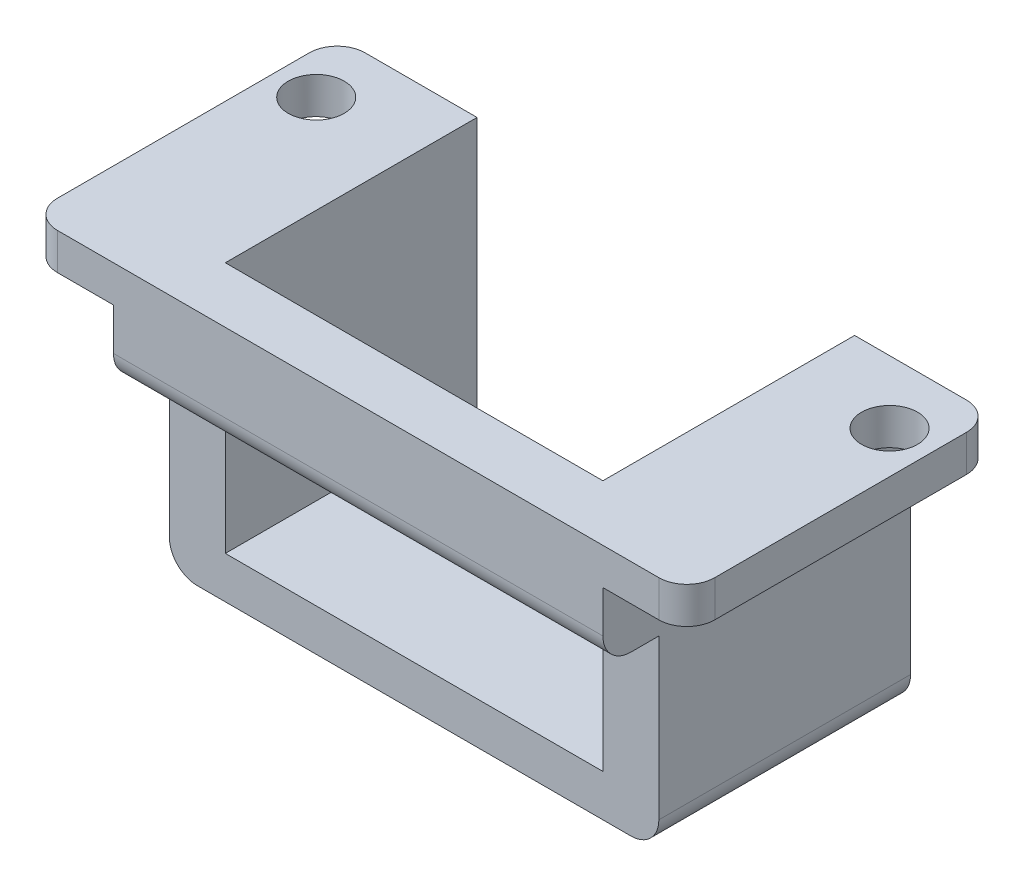
SolidWorks part; units mm, degrees
other "Markup1"
sketch "Sketch8" plane through (0, 0, 27) normal (0, 1, 0) x (-1, 0, 0)
sketch "Sketch10" plane through (0, 0, 22) normal (0, 1, 0) x (-1, 0, 0)
sketch "Sketch11" plane through (0, 0, 22) normal (0, 1, 0) x (-1, 0, 0)
ref_plane "Front Plane" through (0, 0, 0) normal (0, 0, 1) x (1, 0, 0)
ref_plane "Top Plane" through (0, 0, 0) normal (0, 1, 0) x (1, 0, 0)
ref_plane "Right Plane" through (0, 0, 0) normal (1, 0, 0) x (0, 0, -1)
sketch "Sketch1" plane through (0, 0, 0) normal (0, 0, 1) x (1, 0, 0)
  line L0 (0, 0) -> (10, 0)
  line L1 (10, 0) -> (10, -18)
  line L2 (10, -18) -> (37, -18)
  line L3 (37, -18) -> (37, 0)
  line L4 (37, 0) -> (47, 0)
  line L5 (47, 0) -> (47, -2.6145)
  line L6 (47, -2.6145) -> (41, -2.6145)
  line L7 (41, -2.6145) -> (41, -21)
  line L8 (41, -21) -> (6, -21)
  line L9 (6, -21) -> (6, -2.6145)
  line L10 (6, -2.6145) -> (0, -2.6145)
  line L11 (0, -2.6145) -> (0, 0)
  dimension "D1" = 27
  dimension "D2" = 21
  dimension "D3" = 10
  dimension "D4" = 6
  dimension "D5" = 18
extrude "Boss-Extrude1" add sketch "Sketch1" along normal blind 9
sketch "Sketch2" plane through (0, -2.6145, 0) normal (0, -1, 0) x (1, 0, 0)
  line L0 (3, 9) -> (3, 0) construction
  line L1 (0, 9) -> (6, 9) construction
  line L2 (0, 0) -> (6, 0) construction
  line L3 (0, 4.5) -> (6, 4.5) construction
  line L4 (0, 9) -> (0, 0) construction
  line L5 (6, 9) -> (6, 0) construction
  circle A0 centre (3, 4.5) radius 2
  dimension "D1" = 4
ref_plane "Plane1" through (23.5, 0, 0) normal (1, 0, 0) x (0, 0, -1)
extrude "Cut-Extrude1" cut sketch "Sketch2" against normal blind 9
mirror "Mirror1" about plane through (23.5, 0, 0) normal (1, 0, 0) of "Cut-Extrude1"
sketch "Sketch3" plane through (0, 0, 9) normal (0, 0, 1) x (1, 0, 0)
  line L12 (0, 0) -> (0, -2.6145)
  line L13 (0, -2.6145) -> (6, -2.6145)
  line L14 (6, -2.6145) -> (6, -21)
  line L15 (6, -21) -> (41, -21)
  line L16 (41, -21) -> (41, -2.6145)
  line L17 (41, -2.6145) -> (47, -2.6145)
  line L18 (47, -2.6145) -> (47, 0)
  line L19 (47, 0) -> (37, 0)
  line L20 (37, 0) -> (37, -18)
  line L21 (37, -18) -> (10, -18)
  line L22 (10, -18) -> (10, 0)
  line L23 (10, 0) -> (0, 0)
  line L24 (0, 0) -> (0, -2.6145)
  line L25 (0, -2.6145) -> (6, -2.6145)
  line L26 (6, -2.6145) -> (6, -21)
  line L27 (6, -21) -> (41, -21)
  line L28 (41, -21) -> (41, -2.6145)
  line L29 (41, -2.6145) -> (47, -2.6145)
  line L30 (47, -2.6145) -> (47, 0)
  line L31 (47, 0) -> (37, 0)
  line L32 (37, 0) -> (37, -18)
  line L33 (37, -18) -> (10, -18)
  line L34 (10, -18) -> (10, 0)
  line L35 (10, 0) -> (0, 0)
  dimension "D1" = 0
extrude "Boss-Extrude2" add sketch "Sketch3" along normal blind 9
ref_plane "Plane2" through (0, 0, 18) normal (0, 0, 1) x (1, 0, 0)
sketch "Sketch5" plane through (0, 0, 18) normal (0, 0, 1) x (1, 0, 0)
  line L0 (41, -2.6145) -> (47, -2.6145) construction
  line L1 (0, 0) -> (47, 0)
  line L2 (0, 0) -> (0, -2.6145)
  line L3 (0, -2.6145) -> (47, -2.6145)
  line L4 (47, 0) -> (47, -2.6145)
  line L5 (47, -2.6145) -> (47, 0) construction
extrude "Boss-Extrude3" add sketch "Sketch5" along normal blind 4
sketch "Sketch7" plane through (0, -2.6145, 0) normal (0, -1, 0) x (1, 0, 0)
  line L0 (23.5, -11.55) -> (23.5, 11.55) construction
  circle A0 centre (23.5, 22.2422) radius 2
  dimension "D1" = 4
fillet "Fillet1" radius 2 2 edges at (47, -1.3072, 22) (0, -1.3072, 22)
fillet "Fillet4" radius 2 4 edges at (41, -21, 9) (6, -21, 9) (0, -1.3072, 0) (47, -1.3072, 0)
sketch "Sketch9" plane through (0, -2.6145, 0) normal (0, -1, 0) x (1, 0, 0)
  line L0 (0, 18) -> (6, 18)
  line L1 (41, 18) -> (47, 18)
  line L2 (11.55, 18) -> (-11.55, 18) construction
  line L3 (6, 18) -> (6, 22)
  line L4 (41, 18) -> (41, 22)
  line L10 (0, 20) -> (0, 2)
  line L11 (2, 0) -> (6, 0)
  line L12 (6, 0) -> (6, 18)
  line L13 (6, 18) -> (10, 18)
  line L14 (10, 18) -> (37, 18)
  line L15 (37, 18) -> (41, 18)
  line L16 (41, 18) -> (41, 0)
  line L17 (41, 0) -> (45, 0)
  line L18 (47, 2) -> (47, 20)
  line L19 (45, 22) -> (2, 22)
  line L20 (0, 20) -> (0, 2)
  line L21 (2, 0) -> (6, 0)
  line L22 (6, 0) -> (6, 18)
  line L23 (6, 18) -> (10, 18)
  line L24 (10, 18) -> (37, 18)
  line L25 (37, 18) -> (41, 18)
  line L26 (41, 18) -> (41, 0)
  line L27 (41, 0) -> (45, 0)
  line L28 (47, 2) -> (47, 20)
  line L29 (45, 22) -> (2, 22)
  arc A4 (0, 2) -> (2, 0) centre (2, 2) ccw
  arc A5 (45, 0) -> (47, 2) centre (45, 2) ccw
  arc A6 (47, 20) -> (45, 22) centre (45, 20) ccw
  arc A7 (2, 22) -> (0, 20) centre (2, 20) ccw
  arc A8 (0, 2) -> (2, 0) centre (2, 2) ccw
  arc A9 (45, 0) -> (47, 2) centre (45, 2) ccw
  arc A10 (47, 20) -> (45, 22) centre (45, 20) ccw
  arc A11 (2, 22) -> (0, 20) centre (2, 20) ccw
  line M20 (6, 18) -> (10, 18)
  line M21 (10, 18) -> (37, 18)
  line M22 (37, 18) -> (41, 18)
  line M28 (45, 22) -> (2, 22)
  dimension "D1" = 0
extrude "Boss-Extrude5" add sketch "Sketch9" along normal blind 5 contours L4 L3 M22 M28 M20 M21
fillet "Fillet5" radius 2 1 edges at (23.5, -7.6145, 22)
